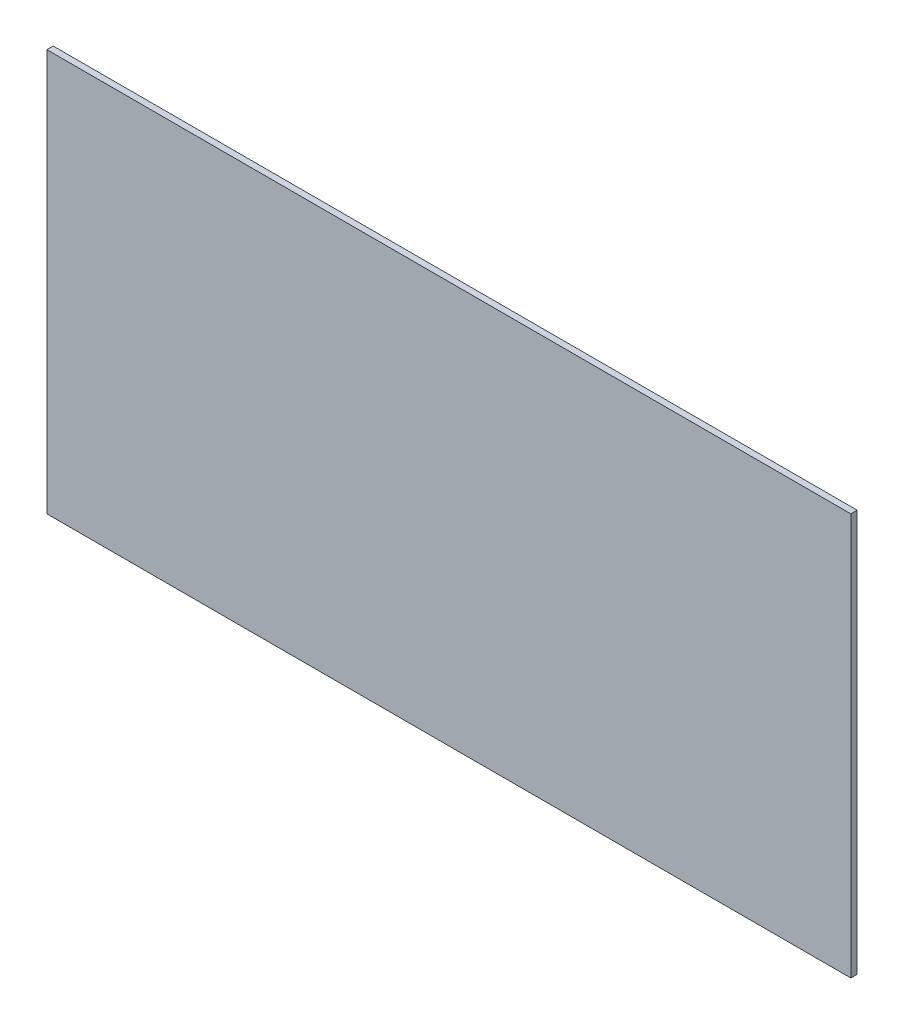
SolidWorks part; units mm, degrees
ref_plane "Front Plane" through (0, 0, 0) normal (0, 0, 1) x (1, 0, 0)
ref_plane "Top Plane" through (0, 0, 0) normal (0, 1, 0) x (1, 0, 0)
ref_plane "Right Plane" through (0, 0, 0) normal (1, 0, 0) x (0, 0, -1)
sketch "Sketch1" plane through (0, 0, 0) normal (0, 0, 1) x (1, 0, 0)
  line L0 (0.635, -0.3175) -> (-0.635, -0.3175)
  line L1 (-0.635, -0.3175) -> (-0.635, 0.3175)
  line L2 (-0.635, 0.3175) -> (0.635, 0.3175)
  line L3 (0.635, 0.3175) -> (0.635, -0.3175)
  line L4 (0, 0) -> (0, -0.4941) construction
  line L5 (0, 0) -> (-0.7534, 0) construction
  dimension "D1" = 1.27
  dimension "D2" = 0.635
extrude "Component_Outline" add sketch "Sketch1" along normal blind 0.01 separate body
sketch3d "3DSketch1"
  line L0 (0, 0, 0) -> (1, 0, 0)
  line L1 (0, 0, 0) -> (0, 1, 0)
  line L2 (0, 0, 0) -> (0, 0, 1)
  point P0 (0, 0, 0)
